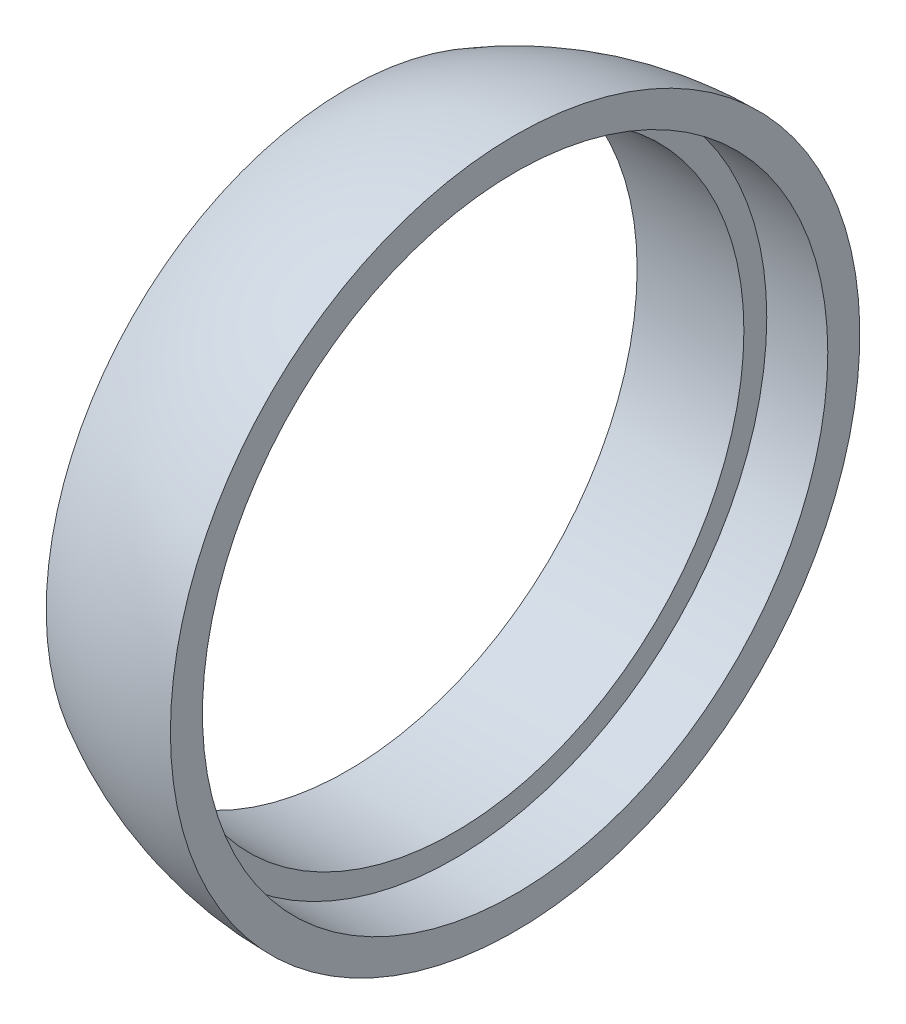
SolidWorks part; units mm, degrees
ref_plane "前视基准面" through (0, 0, 0) normal (0, 0, 1) x (1, 0, 0)
ref_plane "上视基准面" through (0, 0, 0) normal (0, 1, 0) x (1, 0, 0)
ref_plane "右视基准面" through (0, 0, 0) normal (1, 0, 0) x (0, 0, -1)
other "Configuration Table"
sketch "草图1" plane through (0, 0, 0) normal (1, 0, 0) x (0, 0, -1)
  line L0 (0, 11.3) -> (0, -11.3)
  arc A0 (0, 11.3) -> (0, -11.3) centre (0, 0) ccw
  dimension "D1" = 11.3
revolve "旋转1" add sketch "草图1" angle 180 about L0
sketch "草图5" plane through (0, 0, 0) normal (0, 0, 1) x (1, 0, 0)
  line L0 (0, -11.3) -> (0, 11.3) construction
  line L1 (-11.5, 10.097) -> (-5.5, 10.097)
  line L2 (-11.5, 10.097) -> (-11.5, -9.903)
  line L3 (-11.5, -9.903) -> (-5.5, -9.903)
  line L4 (-5.5, 10.097) -> (-5.5, -9.903)
  dimension "D1" = 20
  dimension "D2" = 5.5
  dimension "D3" = 6
extrude "切除-拉伸3" cut sketch "草图5" against normal through all and the other way through all
sketch "草图11" plane through (0, 0, 0) normal (1, 0, 0) x (0, 0, -1)
  circle A0 centre (0, 0) radius 9.5
  dimension "D1" = 19
extrude "切除-拉伸7" cut sketch "草图11" against normal through all
sketch "草图12" plane through (0, 0, 0) normal (1, 0, 0) x (0, 0, -1)
  circle A0 centre (0, 0) radius 10.25
  dimension "D1" = 20.5
extrude "切除-拉伸8" cut sketch "草图12" against normal blind 2
